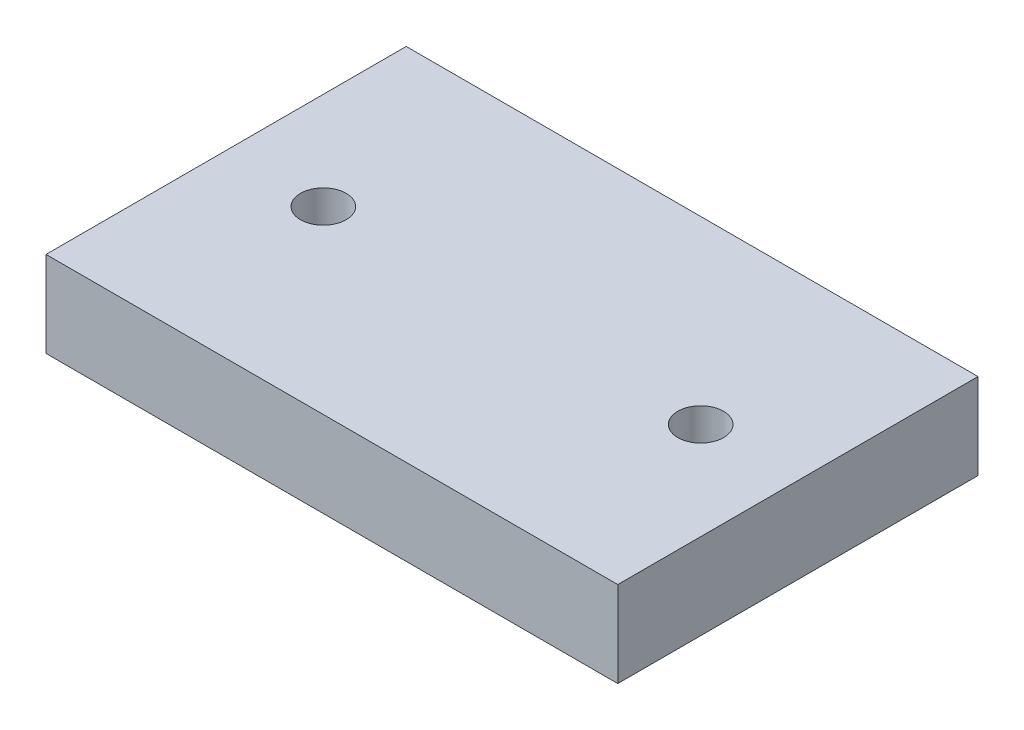
SolidWorks part; units mm, degrees
ref_plane "Alzado" through (0, 0, 0) normal (0, 0, 1) x (1, 0, 0)
ref_plane "Planta" through (0, 0, 0) normal (0, 1, 0) x (1, 0, 0)
ref_plane "Vista lateral" through (0, 0, 0) normal (1, 0, 0) x (0, 0, -1)
sketch "Croquis1" plane through (0, 0, 0) normal (0, 1, 0) x (1, 0, 0)
  line L0 (0, 31.5) -> (100, 31.5) construction
  line L1 (0, 0) -> (100, 0)
  line L2 (0, 0) -> (0, 63)
  line L3 (0, 63) -> (100, 63)
  line L4 (100, 0) -> (100, 63)
  line L5 (50, 63) -> (50, 0) construction
  circle A0 centre (17, 31.5) radius 4
  circle A1 centre (83, 31.5) radius 4
  dimension "D3" = 8
  dimension "D4" = 8
  dimension "D1" = 100
  dimension "D2" = 63
  dimension "D5" = 33
  dimension "D7" = 33
extrude "Saliente-Extruir1" add sketch "Croquis1" along normal blind 15
